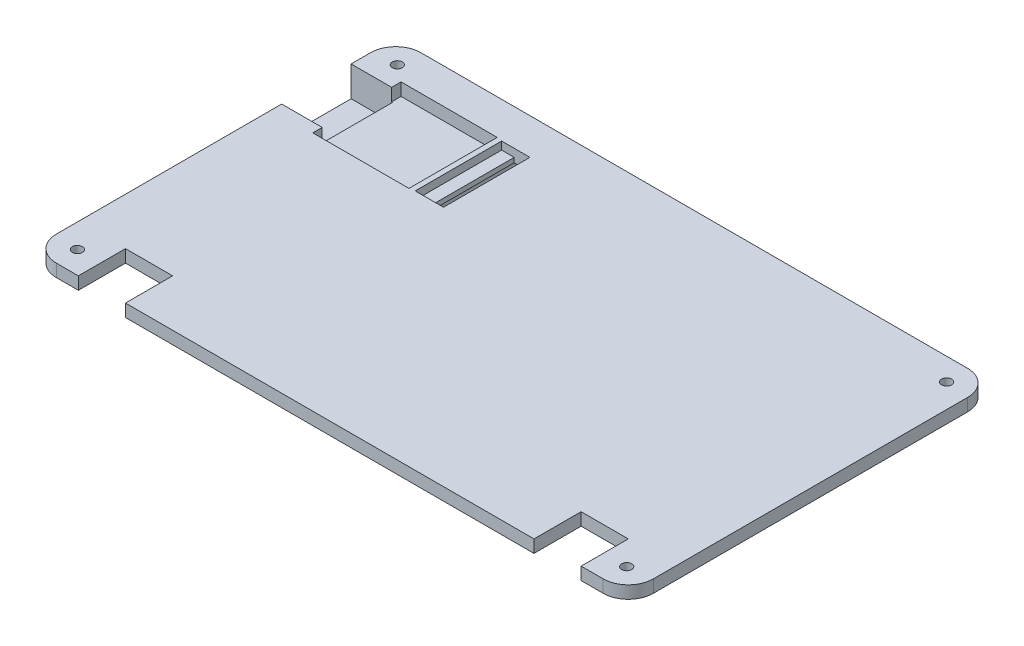
SolidWorks part; units mm, degrees
ref_plane "前视基准面" through (0, 0, 0) normal (0, 0, 1) x (1, 0, 0)
ref_plane "上视基准面" through (0, 0, 0) normal (0, 1, 0) x (1, 0, 0)
ref_plane "右视基准面" through (0, 0, 0) normal (1, 0, 0) x (0, 0, -1)
other "Configuration Table"
sketch "草图1" plane through (0, 0, 0) normal (0, 1, 0) x (1, 0, 0)
  line L1 (-136.2665, -68.2938) -> (136.2665, -68.2938)
  line L2 (-136.2665, -68.2938) -> (-136.2665, 68.2938)
  line L3 (-136.2665, 68.2938) -> (136.2665, 68.2938)
  line L4 (136.2665, -68.2938) -> (136.2665, 68.2938)
  line L5 (-136.2665, -68.2938) -> (136.2665, 68.2938) construction
  line L6 (-136.2665, 68.2938) -> (136.2665, -68.2938) construction
  point P0 (0, 0)
extrude "凸台-拉伸1" add sketch "草图1" along normal blind 4
sketch "草图2" plane through (0, 4, 0) normal (0, 1, 0) x (1, 0, 0)
  line L4 (-87, 58) -> (87, 58) construction
  line L5 (-87, 58) -> (87, 58)
  line L6 (-95, 50) -> (-95, -50)
  line L7 (-87, -58) -> (87, -58)
  line L8 (95, 50) -> (95, -50)
  line L9 (-95, -50) -> (-95, 50) construction
  line L10 (-87, -58) -> (87, -58) construction
  line L11 (95, -50) -> (95, 50) construction
  line L13 (-136.2665, 68.2938) -> (136.2665, 68.2938)
  line L14 (-136.2665, 68.2938) -> (-136.2665, -68.2938)
  line L15 (-136.2665, -68.2938) -> (136.2665, -68.2938)
  line L16 (136.2665, 68.2938) -> (136.2665, -68.2938)
  arc A0 (87, 58) -> (95, 50) centre (87, 50) cw
  arc A1 (-95, -50) -> (-87, -58) centre (-87, -50) ccw
  arc A2 (87, -58) -> (95, -50) centre (87, -50) ccw
  arc A3 (-87, 58) -> (-95, 50) centre (-87, 50) ccw
  dimension "D1" = 8
extrude "切除-拉伸1" cut sketch "草图2" against normal blind 4
sketch "草图3" plane through (0, 0, 0) normal (0, -1, 0) x (1, 0, 0)
  line L0 (-95, -22) -> (-81.8, -22)
  line L1 (-81.8, -22) -> (-81.8, -19)
  line L2 (-81.8, -19) -> (-51.8, -19)
  line L3 (-51.8, -19) -> (-81.8, -19) construction
  line L4 (-51.8, -19) -> (-51.8, -46.5)
  line L5 (-51.8, -46.5) -> (-51.8, -19) construction
  line L6 (-51.8, -46.5) -> (-81.8, -46.5)
  line L7 (-81.8, -46.5) -> (-81.8, -43.5)
  line L8 (-81.8, -43.5) -> (-81.8, -46.5) construction
  line L9 (-81.8, -43.5) -> (-81.8, -22) construction
  line L10 (-81.8, -43.5) -> (-95, -43.5)
  line L11 (-95, -43.5) -> (-95, -22)
extrude "切除-拉伸2" cut sketch "草图3" against normal blind 4
sketch "草图4" plane through (0, 0, 0) normal (0, -1, 0) x (1, 0, 0)
  line L0 (-95, -32.75) -> (-24.4506, -32.75) construction
  line L1 (-95, -43.5) -> (-95, -22) construction
  line L2 (-51.5, -18.7) -> (-51.5, -46.8)
  line L3 (-95, -21.7) -> (-95, -43.8)
  line L4 (-95, -22) -> (-81.8, -22) construction
  line L5 (-81.8, -22) -> (-81.8, -19) construction
  line L6 (-81.8, -19) -> (-51.8, -19) construction
  line L7 (-51.8, -19) -> (-51.8, -46.5) construction
  line L8 (-82.1, -46.8) -> (-51.5, -46.8)
  line L9 (-82.1, -43.8) -> (-82.1, -46.8)
  line L10 (-95, -43.8) -> (-82.1, -43.8)
  line L25 (-95, -21.7) -> (-82.1, -21.7)
  line L26 (-95, -22) -> (-95, 50) construction
  line L27 (-82.1, -21.7) -> (-82.1, -18.7)
  line L28 (-82.1, -18.7) -> (-51.5, -18.7)
  point P19 (-51.5, -32.75)
  dimension "D1" = 0.3
  dimension "D2" = 0.3
  dimension "D3" = 0.3
  dimension "D4" = 0.3
extrude "切除-拉伸3" cut sketch "草图4" against normal blind 4 contours L28 L2 L8 L9 L10 L3 L25 L27
sketch "草图5" plane through (0, 0, 0) normal (0, -1, 0) x (1, 0, 0)
  line L0 (-81.8, -43.5) -> (-81.8, -22) construction
  line L1 (-47.8, -50.75) -> (-81.8, -50.75)
  line L2 (-47.8, -50.75) -> (-47.8, -14.75)
  line L3 (-47.8, -14.75) -> (-81.8, -14.75)
  line L4 (-81.8, -50.75) -> (-81.8, -14.75)
  line L5 (-47.8, -50.75) -> (-81.8, -14.75) construction
  line L6 (-47.8, -14.75) -> (-81.8, -50.75) construction
  line L7 (-95, -32.75) -> (-25.646, -32.75) construction
  line L8 (-95, -22) -> (-95, -43.5) construction
  line L9 (-51.8, -46.5) -> (-51.8, -19) construction
  point P0 (-64.8, -32.75)
  dimension "D1" = 36
  dimension "D2" = 4
extrude "凸台-拉伸2" add sketch "草图5" along normal blind 4 contours L3 L4 L1 L2
sketch "草图6" plane through (0, 0, 0) normal (0, -1, 0) x (1, 0, 0)
  line L0 (-81.8, -18.7) -> (-81.8, -14.75) construction
  line L9 (-95, -21.7) -> (-81.8, -21.7)
  line L10 (-95, -21.7) -> (-95, -17.7)
  line L11 (-95, -17.7) -> (-81.8, -17.7)
  line L12 (-81.8, -21.7) -> (-81.8, -17.7)
  line L13 (-81.8, -50.75) -> (-81.8, -46.8) construction
  line L14 (-95, -43.8) -> (-81.8, -43.8)
  line L15 (-95, -43.8) -> (-95, -47.8)
  line L16 (-95, -47.8) -> (-81.8, -47.8)
  line L17 (-81.8, -43.8) -> (-81.8, -47.8)
  dimension "D1" = 4
  dimension "D2" = 4
extrude "凸台-拉伸3" add sketch "草图6" along normal blind 5.6
sketch "草图7" plane through (0, -5.6, 0) normal (0, -1, 0) x (1, 0, 0)
  line L0 (-95, -47.8) -> (-81.8, -47.8) construction
  line L5 (-95, -17.7) -> (-77.8, -17.7)
  line L6 (-95, -17.7) -> (-95, -47.8)
  line L7 (-95, -47.8) -> (-77.8, -47.8)
  line L8 (-77.8, -17.7) -> (-77.8, -47.8)
  line L9 (-81.8, -43.5) -> (-81.8, -22) construction
  dimension "D1" = 4
extrude "凸台-拉伸4" add sketch "草图7" along normal blind 4
sketch "草图8" plane through (0, 4, 0) normal (0, 1, 0) x (1, 0, 0)
  line L1 (-81.8, 19) -> (-45.8, 19) construction
  line L2 (-45.8, 46.5) -> (-40.8, 46.5)
  line L3 (-45.8, 46.5) -> (-45.8, 19)
  line L4 (-45.8, 19) -> (-40.8, 19)
  line L5 (-40.8, 46.5) -> (-40.8, 19)
  dimension "D1" = 5
extrude "切除-拉伸4" cut sketch "草图8" against normal blind 4
sketch "草图9" plane through (-45.8, 0, 0) normal (1, 0, 0) x (0, 0, -1)
  line L0 (19, -0.1) -> (19, 6.4) construction
  line L1 (19, 4) -> (46.5, 4)
  line L2 (19, 4) -> (19, 1.5)
  line L3 (19, 1.5) -> (46.5, 1.5)
  line L4 (46.5, 4) -> (46.5, 1.5)
  line L5 (7.5, 4) -> (21.5, 4) construction
  line L6 (46.5, 6.4) -> (46.5, 7.9) construction
  dimension "D1" = 2.5
extrude "切除-拉伸5" cut sketch "草图9" against normal blind 4
sketch "草图10" plane through (0, 4, 0) normal (0, 1, 0) x (1, 0, 0)
  circle A0 centre (87.4, 50.9) radius 1.6
  circle A1 centre (-87.4, 50.9) radius 1.6
  circle A2 centre (-87.4, -50.9) radius 1.6
  circle A3 centre (87.4, -50.9) radius 1.6
extrude "切除-拉伸6" cut sketch "草图10" against normal blind 10
sketch "草图11" plane through (0, 0, 0) normal (0, -1, 0) x (1, 0, 0)
  circle A0 centre (-25.1444, 10.5195) radius 2.75
  circle A1 centre (-25.1444, -25.6005) radius 2.75
  circle A2 centre (65.0572, 10.5195) radius 2.75
  circle A3 centre (65.0572, -25.6005) radius 2.75
  dimension "D1" = 5.5
  dimension "D2" = 5.5
  dimension "D3" = 5.5
  dimension "D4" = 5.5
sketch "草图13" plane through (0, 0, 0) normal (0, -1, 0) x (1, 0, 0)
  line L0 (-87, 58) -> (87, 58) construction
  line L1 (80, 58) -> (65, 58)
  line L2 (80, 58) -> (80, 43)
  line L3 (80, 43) -> (65, 43)
  line L4 (65, 58) -> (65, 43)
  line L5 (0, 0) -> (0, 58) construction
  line L6 (95, 50) -> (95, -50) construction
  line L7 (-80, 43) -> (-65, 43)
  line L8 (-65, 58) -> (-65, 43)
  line L9 (-80, 58) -> (-65, 58)
  line L10 (-80, 58) -> (-80, 43)
  dimension "D1" = 15
  dimension "D2" = 15
  dimension "D3" = 15
extrude "切除-拉伸7" cut sketch "草图13" against normal mid plane 10
